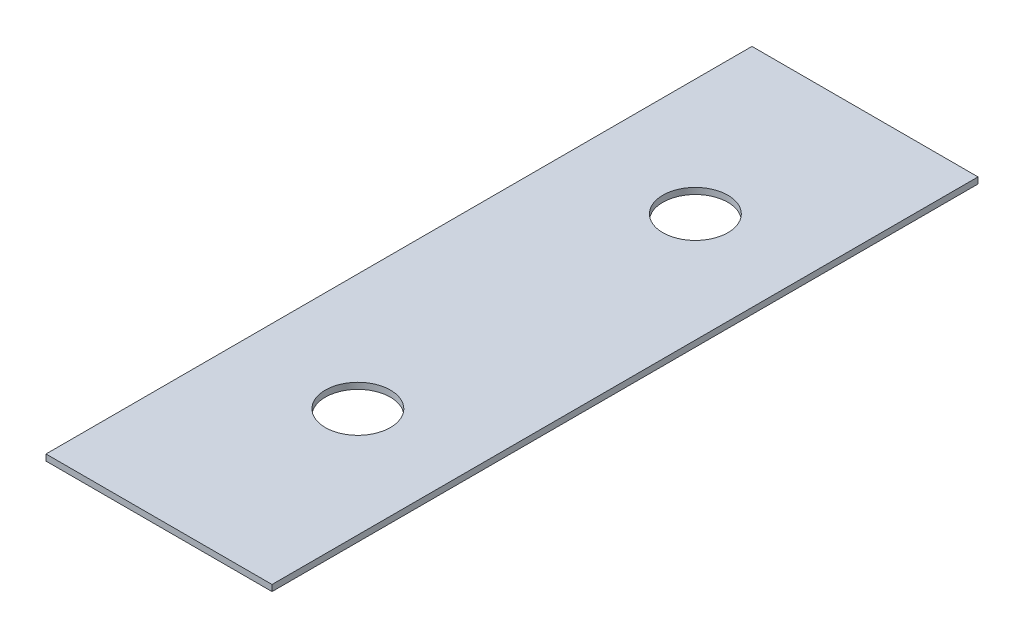
SolidWorks part; units mm, degrees
ref_plane "Front Plane" through (0, 0, 0) normal (0, 0, 1) x (1, 0, 0)
ref_plane "Top Plane" through (0, 0, 0) normal (0, 1, 0) x (1, 0, 0)
ref_plane "Right Plane" through (0, 0, 0) normal (1, 0, 0) x (0, 0, -1)
sketch "Sketch1" plane through (0, 0, 0) normal (0, 1, 0) x (1, 0, 0)
  line L1 (0, 0) -> (-73, 0)
  line L2 (0, 0) -> (0, -228)
  line L3 (0, -228) -> (-73, -228)
  line L4 (-73, 0) -> (-73, -228)
  dimension "D1" = 73
  dimension "D2" = 228
extrude "Boss-Extrude1" add sketch "Sketch1" along normal blind 2
sketch "Sketch2" plane through (0, 2, 0) normal (0, 1, 0) x (1, 0, 0)
  line L0 (-73, -228) -> (0, -228) construction
  line L1 (0, 0) -> (-73, 0) construction
  circle A0 centre (-35.2792, -56) radius 10.5
  circle A1 centre (-35.2792, -165) radius 10.5
  dimension "D1" = 21
  dimension "D2" = 21
  dimension "D3" = 63
  dimension "D4" = 56
extrude "Cut-Extrude1" cut sketch "Sketch2" against normal blind 2
